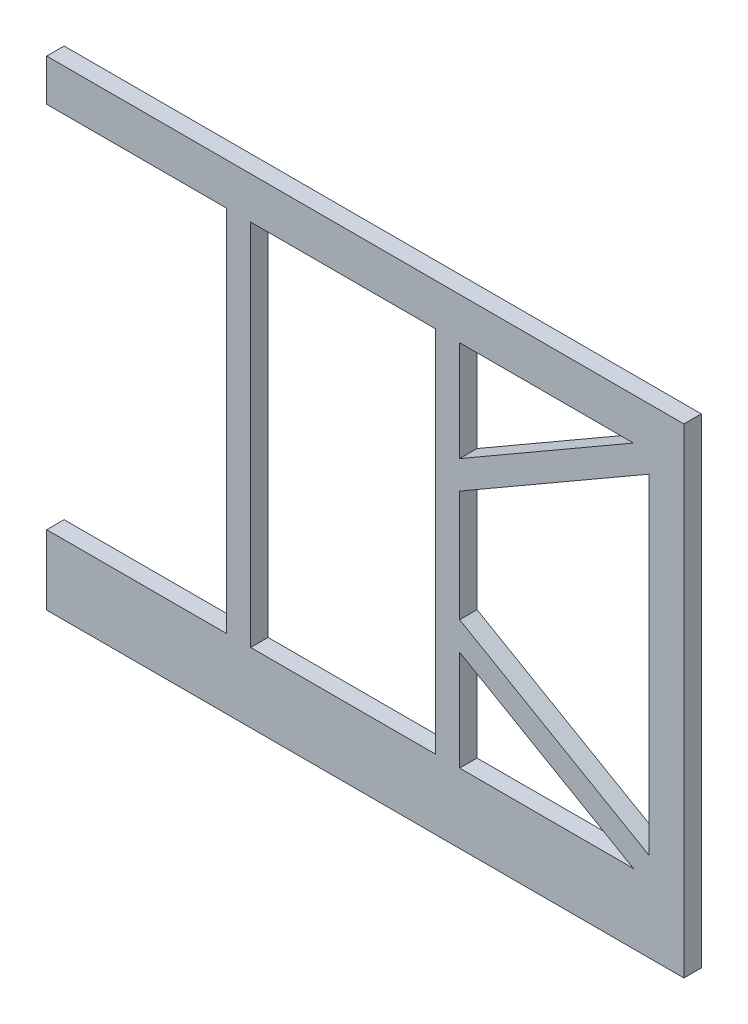
SolidWorks part; units mm, degrees
ref_plane "Front Plane" through (0, 0, 0) normal (0, 0, 1) x (1, 0, 0)
ref_plane "Top Plane" through (0, 0, 0) normal (0, 1, 0) x (1, 0, 0)
ref_plane "Right Plane" through (0, 0, 0) normal (1, 0, 0) x (0, 0, -1)
sketch "Sketch1" plane through (0, 0, 0) normal (0, 0, 1) x (1, 0, 0)
  line L0 (56.5, 51.9) -> (3.5, 51.9)
  line L1 (127.9, 63.9) -> (-55.0824, 63.9)
  line L2 (127.9, 63.9) -> (127.9, 51.9)
  line L3 (113.4127, 51.9) -> (63.5, 51.9)
  line L4 (-55.0824, 63.9) -> (-55.0824, 51.9)
  line L5 (-52.075, 51.9) -> (-42.9, 51.9) construction
  line L6 (-55.0824, -191.7) -> (-55.0824, 63.9) construction
  line L7 (127.9, -63.9) -> (127.9, 63.9) construction
  line L8 (113.4127, -53.9) -> (63.5, -53.9)
  line L10 (127.9, -73.9) -> (-55.0824, -73.9)
  line L11 (-55.0824, -53.9) -> (-55.0824, -73.9)
  line L13 (-42.9, -53.9) -> (-52.075, -53.9) construction
  line L14 (56.5, 51.9) -> (56.5, -53.9)
  line L16 (127.9, 51.9) -> (127.9, -73.9)
  line L18 (117.9, 46.4079) -> (117.9, -48.4079)
  line L20 (63.5, 51.9) -> (63.5, 23.0829)
  line L21 (56.5, -53.9) -> (3.5, -53.9)
  line L22 (-3.5, 51.9) -> (-55.0824, 51.9)
  line L24 (-3.5, 51.9) -> (-3.5, -53.9)
  line L26 (3.5, 51.9) -> (3.5, -53.9)
  line L27 (-3.5, -53.9) -> (-55.0824, -53.9)
  line L28 (113.4127, -53.9) -> (63.5, -25.0829)
  line L29 (63.5, -17) -> (117.9, -48.4079)
  line L30 (127.9, 0) -> (-58.5, 0) construction
  line L31 (113.4127, 51.9) -> (63.5, 23.0829)
  line L32 (117.9, 46.4079) -> (63.5, 15)
  line L33 (63.5, 15) -> (63.5, -17)
  line L34 (63.5, -25.0829) -> (63.5, -53.9)
  arc A0 (-59.8766, -1.4949) -> (-59.8766, 1.4949) centre (-60, 0) ccw construction
  circle A1 centre (60, 56) radius 0.3125 construction
  dimension "D1" = 20
  dimension "D2" = 10
  dimension "D3" = 7
  dimension "D4" = 3.5
  dimension "D5" = 7
  dimension "D6" = 3.5
  dimension "D7" = 30
  dimension "D8" = 7
  dimension "D9" = 15
  dimension "D10" = 30
  dimension "D11" = 7
  dimension "D12" = 17
extrude "Boss-Extrude1" add sketch "Sketch1" along normal blind 5
